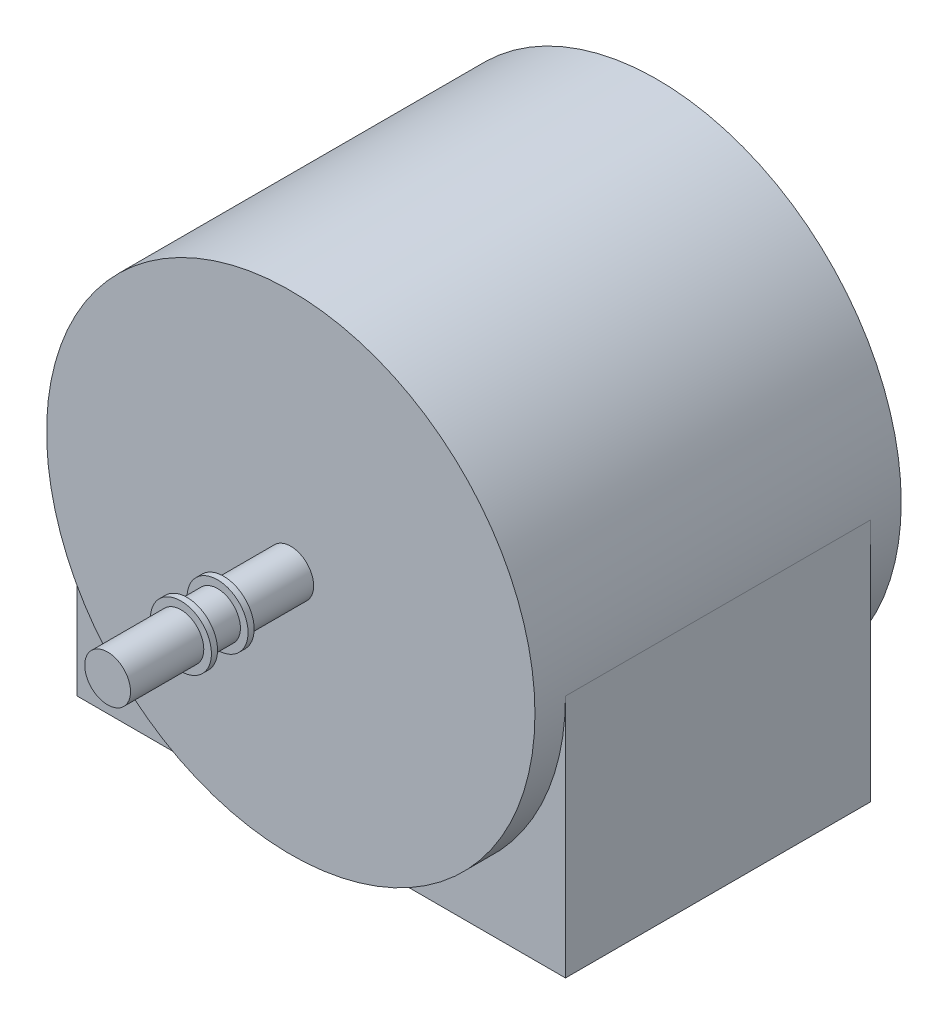
SolidWorks part; units mm, degrees
ref_plane "Ön Düzlem" through (0, 0, 0) normal (0, 0, 1) x (1, 0, 0)
ref_plane "Üst Düzlem" through (0, 0, 0) normal (0, 1, 0) x (1, 0, 0)
ref_plane "Sağ Düzlem" through (0, 0, 0) normal (1, 0, 0) x (0, 0, -1)
sketch "Çizim2" plane through (0, 0, 0) normal (0, 0, 1) x (1, 0, 0)
  circle A0 centre (0, 0) radius 80
  dimension "D1" = 160
extrude "Yükseklik-Ekstrüzyon1" add sketch "Çizim2" along normal blind 120 contours A0
sketch "Çizim3" plane through (0, 0, 0) normal (0, 0, 1) x (1, 0, 0)
  line L0 (-80, 0) -> (-80, -80)
  line L1 (-80, -80) -> (80, -80)
  line L2 (80, -80) -> (80, 0)
  arc A0 (-80, 0) -> (80, 0) centre (0, 0) ccw
extrude "Yükseklik-Ekstrüzyon3" add sketch "Çizim3" along normal blind 100 from offset 10 contours A0 L1 L2 | A0 L0 L1
sketch "Çizim5" plane through (0, -80, 0) normal (0, -1, 0) x (1, 0, 0)
  line L0 (0, 0) -> (0, 120) construction
  line L1 (-80, 0) -> (80, 0) construction
  line L2 (80, 120) -> (-80, 120) construction
  line L3 (80, 60) -> (-80, 60) construction
  line L4 (80, 110) -> (80, 10) construction
  line L5 (-80, 110) -> (-80, 10) construction
  line L6 (30, 90) -> (30, 60) construction
  line L7 (30, 90) -> (0, 90) construction
  line L8 (-30, 90) -> (0, 60) construction
  circle A1 centre (30, 90) radius 5
  circle A2 centre (30, 30) radius 5
  circle A3 centre (-30, 90) radius 5
  circle A4 centre (-30, 30) radius 5
  dimension "D1" = 10
  dimension "D2" = 30
  dimension "D3" = 30
extrude "Yükseklik-Ekstrüzyon4" add sketch "Çizim5" along normal blind 5
sketch "Çizim8" plane through (0, 0, 120) normal (0, 0, 1) x (1, 0, 0)
  circle A0 centre (0, 0) radius 7.5
  dimension "D1" = 15
extrude "Yükseklik-Ekstrüzyon6" add sketch "Çizim8" along normal blind 60
sketch "Çizim9" plane through (0, 0, 120) normal (0, 0, 1) x (1, 0, 0)
  circle A0 centre (0, 0) radius 10
  dimension "D1" = 20
extrude "Yükseklik-Ekstrüzyon7" add sketch "Çizim9" against normal blind 2 from offset 24 contours A0
sketch "Çizim10" plane through (0, 0, 144) normal (0, 0, 1) x (1, 0, 0)
  circle A0 centre (0, 0) radius 10
extrude "Yükseklik-Ekstrüzyon8" add sketch "Çizim10" along normal blind 2 from offset 10
